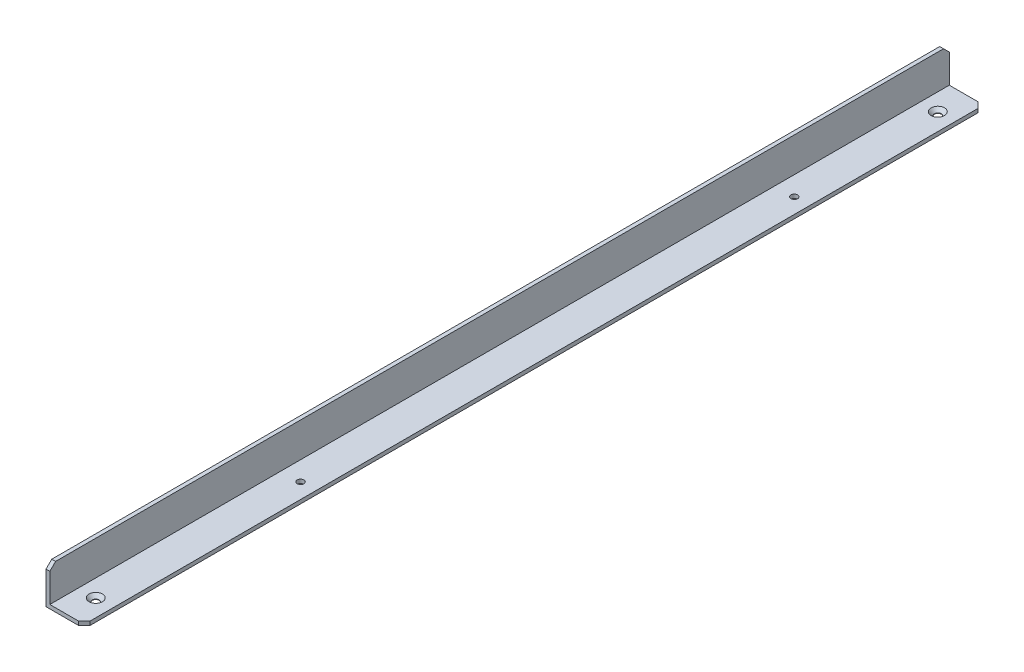
SolidWorks part; units mm, degrees
material "Aluminium"
ref_plane "Front Plane" through (0, 0, 0) normal (0, 0, 1) x (1, 0, 0)
ref_plane "Top Plane" through (0, 0, 0) normal (0, 1, 0) x (1, 0, 0)
ref_plane "Right Plane" through (0, 0, 0) normal (1, 0, 0) x (0, 0, -1)
sketch "Sketch1" plane through (0, 0, 0) normal (0, 0, 1) x (1, 0, 0)
  line L1 (0, 0) -> (20, 0)
  line L2 (0, 0) -> (0, 20)
  line L3 (0, 20) -> (2, 20)
  line L4 (20, 0) -> (20, 2)
  line L7 (20, 2) -> (2, 2)
  line L8 (2, 20) -> (2, 2)
  dimension "D1" = 20
  dimension "D2" = 2
extrude "Boss-Extrude1" add sketch "Sketch1" along normal mid plane 470
sketch "Sketch2" plane through (0, 2, 0) normal (0, 1, 0) x (1, 0, 0)
  line L0 (11, -220) -> (11, -235) construction
  line L1 (20, -235) -> (2, -235) construction
  line L2 (11, 235) -> (11, 220) construction
  line L3 (20, 235) -> (2, 235) construction
  circle A0 centre (11, 220) radius 3.5
  circle A1 centre (11, -220) radius 3.5
  dimension "D1" = 15
  dimension "D2" = 7
extrude "Cut-Extrude1" cut sketch "Sketch2" against normal blind 450 draft 45
sketch "Sketch3" plane through (0, 2, 0) normal (0, 1, 0) x (1, 0, 0)
  circle A0 centre (11, -220) radius 1.75
  circle A1 centre (11, 220) radius 1.75
  dimension "D1" = 3.5
extrude "Cut-Extrude2" cut sketch "Sketch3" against normal through all
ref_plane "Plane1" through (0, 0, 0) normal (0.7071, -0.7071, 0) x (0, 0, -1)
mirror "Mirror1" [suppressed] about plane through (0, 0, 0) normal (0.7071, -0.7071, 0)
chamfer "Chamfer1" distance 3 angle 45 4 edges at (20, 1, -235) (1, 20, -235) (20, 1, 235) (1, 20, 235)
sketch "Sketch4" plane through (0, 2, 0) normal (0, 1, 0) x (1, 0, 0)
  line L0 (12, -114) -> (12, 144) construction
  line L1 (20, -232) -> (20, 232) construction
  line L2 (17, 235) -> (2, 235) construction
  circle A0 centre (12, 144) radius 1.75
  circle A1 centre (12, -114) radius 1.75
  dimension "D1" = 258
  dimension "D2" = 3.5
  dimension "D4" = 91
  dimension "D3" = 8
extrude "Cut-Extrude3" cut sketch "Sketch4" against normal through all
